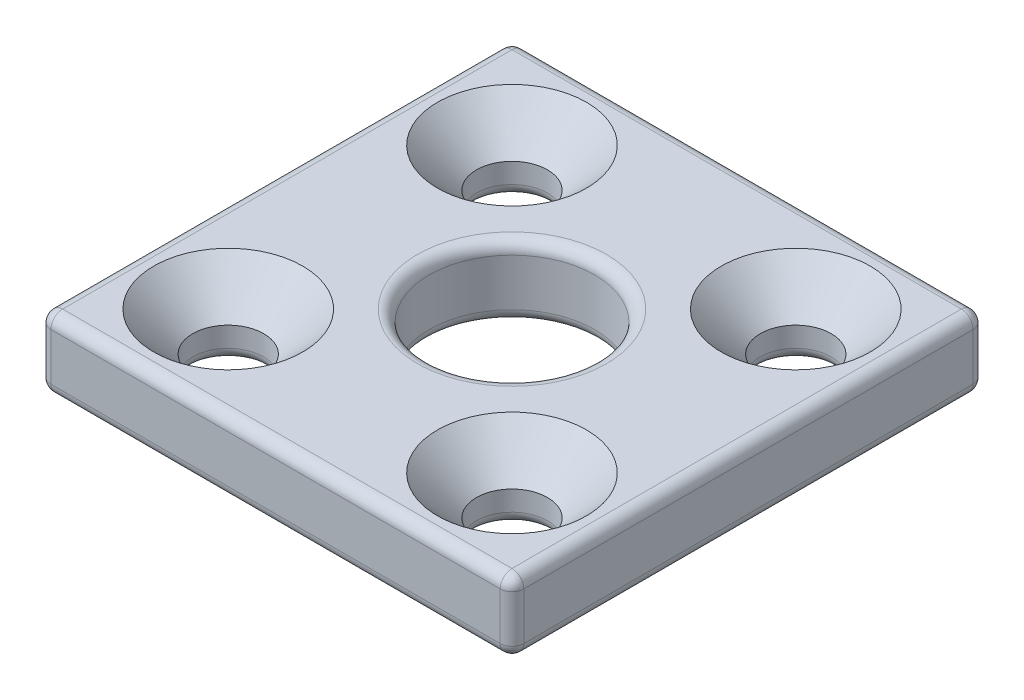
SolidWorks part; units mm, degrees
ref_plane "Front Plane" through (0, 0, 0) normal (0, 0, 1) x (1, 0, 0)
ref_plane "Top Plane" through (0, 0, 0) normal (0, 1, 0) x (1, 0, 0)
ref_plane "Right Plane" through (0, 0, 0) normal (1, 0, 0) x (0, 0, -1)
sketch "Sketch1" plane through (0, 0, 0) normal (0, 1, 0) x (1, 0, 0)
  line L0 (0, 10) -> (20, 10) construction
  line L1 (0, 0) -> (20, 0)
  line L2 (0, 0) -> (0, 20)
  line L3 (0, 20) -> (20, 20)
  line L4 (20, 0) -> (20, 20)
  line L5 (10, 20) -> (10, 0) construction
  line L6 (20, 20) -> (0, 0) construction
  circle A0 centre (16, 16) radius 1.5
  circle A1 centre (4, 16) radius 1.5
  circle A2 centre (16, 4) radius 1.5
  circle A3 centre (4, 4) radius 1.5
  circle A4 centre (10, 10) radius 3.5
  dimension "D2" = 3
  dimension "D4" = 7
  dimension "D1" = 20
  dimension "D3" = 4
extrude "Boss-Extrude1" add sketch "Sketch1" along normal blind 3
chamfer "Chamfer1" distance 1.65 angle 45 4 edges at (16, 3, -5.5) (4, 3, -2.5) (4, 3, -17.5) (16, 3, -14.5)
fillet "Fillet1" radius 0.5 18 edges at (16, 0, -5.5) (16, 0, -14.5) (4, 0, -17.5) (4, 0, -2.5) (10, 0, -6.5) (10, 3, -6.5) (20, 3, -10) (20, 0, -10) (20, 1.5, -20) (10, 3, -20) (10, 0, -20) (0, 1.5, -20) (0, 3, -10) (0, 0, -10) (0, 1.5, 0) (10, 3, 0) (20, 1.5, 0) (10, 0, 0)
